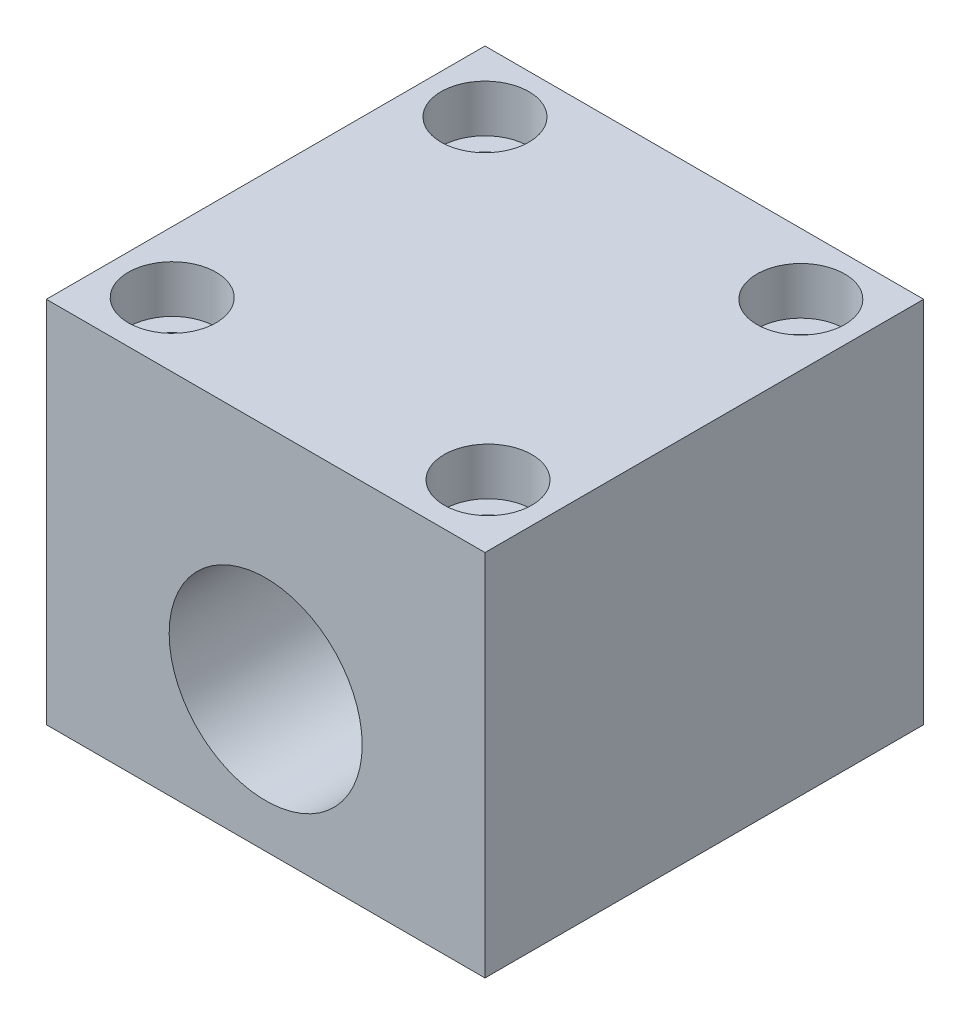
SolidWorks part; units mm, degrees
ref_plane "Спереди" through (0, 0, 0) normal (0, 0, 1) x (1, 0, 0)
ref_plane "Сверху" through (0, 0, 0) normal (0, 1, 0) x (1, 0, 0)
ref_plane "Справа" through (0, 0, 0) normal (1, 0, 0) x (0, 0, -1)
sketch "Эскиз1" plane through (0, 0, 0) normal (0, 0, 1) x (1, 0, 0)
  line L0 (-25, 21) -> (0, 21)
  line L1 (25, 21) -> (25, -21)
  line L3 (25, -21) -> (-25, -21)
  line L5 (-25, -21) -> (-25, 21)
  line L6 (0, 21) -> (25, 21)
  line L7 (0, 21) -> (0, 0) construction
  line L8 (0, 0) -> (0, -21) construction
  dimension "D4" = 50
  dimension "D5" = 42
extrude "База" add sketch "Эскиз1" against normal blind 50
sketch "Эскиз2" plane through (0, 0, -50) normal (0, 0, -1) x (-1, 0, 0)
  circle A0 centre (0, -5) radius 11
  dimension "D1" = 22
  dimension "D2" = 5
extrude "Вырез-Вытянуть1" cut sketch "Эскиз2" against normal blind 14
sketch "Эскиз3" plane through (0, 0, 0) normal (0, 0, 1) x (1, 0, 0)
  circle A0 centre (0, -5) radius 11
  circle A1 centre (0, -5) radius 11 construction
extrude "Вырез-Вытянуть2" cut sketch "Эскиз3" against normal blind 30
sketch "Эскиз4" plane through (0, 0, 0) normal (0, 0, 1) x (1, 0, 0)
  circle A0 centre (0, -5) radius 6.5
  dimension "D1" = 13
extrude "Вырез-Вытянуть3" cut sketch "Эскиз4" against normal through all
hole_wizard "Крепление M5" positions "Эскиз5" profile "Эскиз7" counterbore size "M5" standard "ISO" end condition through all
sketch "Эскиз5" plane through (0, 21, 0) normal (0, 1, 0) x (1, 0, 0)
  line L1 (-18, 43) -> (-18, 50) construction
  line L2 (25, 50) -> (-25, 50) construction
  line L5 (-18, 43) -> (-25, 43) construction
  line L6 (-25, 50) -> (-25, 0) construction
  line L11 (18, 43) -> (25, 43) construction
  line L12 (25, 50) -> (25, 0) construction
  point P0 (-18, 43)
  point P2 (-18, 7.3448)
  point P4 (18, 7.3448)
  point P6 (18, 43)
  dimension "D1" = 7
sketch "Эскиз7" plane through (-18, 21, -43) normal (1, 0, 0) x (0, 0, 1)
  line L0 (0, 0) -> (0, 42)
  line L1 (0, 42) -> (2.75, 42)
  line L3 (2.75, 42) -> (2.75, 5.4)
  line L4 (2.75, 5.4) -> (5, 5.4)
  line L5 (5, 5.4) -> (5, 0)
  line L7 (5, 0) -> (0, 0)
  line L11 (0, -6.35) -> (0, 107.95) construction
  dimension "Диаметр сквозного отверстия" = 5.5
  dimension "Глубина сквозного отверстия" = 42
  dimension "Диаметр цековки" = 10
  dimension "Глубина цековки" = 5.4
